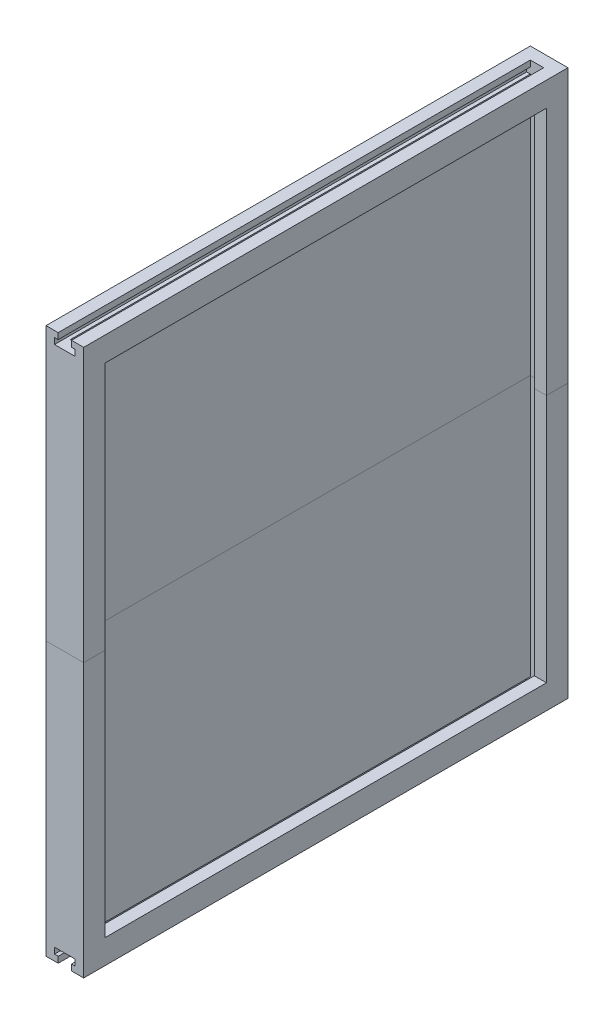
SolidWorks part; units mm, degrees
ref_plane "Front Plane" through (0, 0, 0) normal (1, 0, 0) x (0, 1, 0)
ref_plane "Top Plane" through (0, 0, 0) normal (0, 0, 1) x (0, 1, 0)
ref_plane "Right Plane" through (0, 0, 0) normal (0, 1, 0) x (-1, 0, 0)
sketch "Sketch1" plane through (0, 0, 0) normal (1, 0, 0) x (0, 1, 0)
  line L1 (-225, -199.5) -> (225, -199.5)
  line L2 (-225, -199.5) -> (-225, 199.5)
  line L3 (-225, 199.5) -> (225, 199.5)
  line L4 (225, -199.5) -> (225, 199.5)
  line L5 (-225, -199.5) -> (225, 199.5) construction
  line L6 (-225, 199.5) -> (225, -199.5) construction
  point P0 (0, 0)
  dimension "D1" = 399
  dimension "D2" = 450
extrude "Boss-Extrude1" add sketch "Sketch1" along normal blind 10
sketch "Sketch3" plane through (10, 0, 0) normal (1, 0, 0) x (0, 1, 0)
  line L19 (-225, -199.5) -> (225, -199.5)
  line L20 (-225, -199.5) -> (-225, 199.5)
  line L21 (-225, 199.5) -> (225, 199.5)
  line L22 (225, -199.5) -> (225, 199.5)
  line L23 (-225, -199.5) -> (225, 199.5) construction
  line L24 (-225, 199.5) -> (225, -199.5) construction
  line L25 (-215, -189.5) -> (215, -189.5)
  line L26 (-215, -189.5) -> (-215, 189.5)
  line L27 (-215, 189.5) -> (215, 189.5)
  line L28 (215, -189.5) -> (215, 189.5)
  line L29 (-215, -189.5) -> (215, 189.5) construction
  line L30 (-215, 189.5) -> (215, -189.5) construction
  point P0 (0, 0)
  point P6 (0, 0)
  dimension "D1" = 10
  dimension "D2" = 10
extrude "Boss-Extrude2" add sketch "Sketch3" along normal blind 11
sketch "Sketch5" plane through (21, 0, 0) normal (1, 0, 0) x (0, 1, 0)
  line L1 (-225, -199.5) -> (225, -199.5)
  line L2 (-225, -199.5) -> (-225, 199.5)
  line L3 (-225, 199.5) -> (225, 199.5)
  line L4 (225, -199.5) -> (225, 199.5)
  line L5 (-225, -199.5) -> (225, 199.5) construction
  line L6 (-225, 199.5) -> (225, -199.5) construction
  line L7 (-205, -181.7667) -> (205, -181.7667)
  line L8 (-205, -181.7667) -> (-205, 181.7667)
  line L9 (-205, 181.7667) -> (205, 181.7667)
  line L10 (205, -181.7667) -> (205, 181.7667)
  line L11 (-205, -181.7667) -> (205, 181.7667) construction
  line L12 (-205, 181.7667) -> (205, -181.7667) construction
  point P0 (0, 0)
  point P7 (0, 0)
  dimension "D1" = 20
extrude "Boss-Extrude3" add sketch "Sketch5" along normal blind 10
sketch "Sketch7" plane through (0, 0, 199.5) normal (0, 0, 1) x (1, 0, 0)
  line L0 (0, -215) -> (31, -215) construction
  line L1 (0, 225) -> (0, -225) construction
  line L2 (31, 225) -> (31, -225) construction
  line L3 (31, -225) -> (0, -225) construction
  line L4 (-191.7844, 0) -> (49808.2156, 0) construction
  line L5 (10, -225) -> (21, -225)
  line L6 (10, -225) -> (10, -220)
  line L7 (10, -220) -> (21, -220)
  line L8 (21, -225) -> (21, -220)
  line L9 (24, -220) -> (7, -220)
  line L10 (24, -220) -> (24, -215)
  line L11 (24, -215) -> (7, -215)
  line L12 (7, -220) -> (7, -215)
  line L13 (31, 225) -> (0, 225) construction
  line L14 (0, 215) -> (31, 215) construction
  line L15 (7, 220) -> (7, 215)
  line L16 (24, 215) -> (7, 215)
  line L17 (24, 220) -> (24, 215)
  line L18 (24, 220) -> (7, 220)
  line L19 (21, 225) -> (21, 220)
  line L20 (10, 220) -> (21, 220)
  line L21 (10, 225) -> (10, 220)
  line L22 (10, 225) -> (21, 225)
  line M8 (0, -225) -> (31, -225)
  line M10 (31, 225) -> (0, 225)
  dimension "D1" = 10
  dimension "D2" = 11
  dimension "D3" = 10
  dimension "D4" = 5
  dimension "D5" = 17
  dimension "D6" = 3
  dimension "D7" = 225
extrude "Cut-Extrude1" cut sketch "Sketch7" against normal blind 389 contours L8 L7 L6 M8 | L12 L9 L7 L10 L11 | L21 L18 L19 M10 | L17 L18 L15 L16
sketch "Sketch8" plane through (0, 0, 199.5) normal (0, 0, 1) x (1, 0, 0)
  line L0 (-127.5985, 0) -> (127.5985, 0) construction
  line L2 (0, 0) -> (31, 0)
  line L3 (31, 225) -> (31, -225) construction
  point P4 (0, 0)
split "Split1" trim tools "Sketch8" bodies to split 104 resulting bodies 105 106
equation "\"CD_Height\"= 125mm"
equation "\"CD_Thickness\"= 10mm"
equation "\"CD_Width\"= 142mm"
equation "\"Wall_Thickness\"= 10mm"
equation "\"Total_Height\"= 3 * \"CD_Height\" + 2 * \"Wall_Thickness\" + 4mm"
equation "\"Total_Width\"= \"CD_Width\" * 3 + \"Wall_Thickness\" * 2 + 4mm"
equation "\"Tolerance\"= 1mm"
equation "\"D2@Sketch1\"= \"Total_Width\""
equation "\"D1@Sketch1\"= \"Total_Height\""
equation "\"D1@Sketch3\"=\"Wall_Thickness\""
equation "\"D2@Sketch3\"=\"Wall_Thickness\""
equation "\"D1@Boss-Extrude2\"=\"CD_Thickness\"+\"Tolerance\""
equation "\"Overhang_Width\"= 10mm"
equation "\"D1@Sketch5\"=\"Wall_Thickness\"+\"Overhang_Width\""
equation "\"D1@Boss-Extrude3\"=\"Wall_Thickness\""
equation "\"D1@Sketch7\"=\"Wall_Thickness\""
equation "\"D3@Sketch7\"=\"Wall_Thickness\""
equation "\"D2@Sketch7\"=\"Wall_Thickness\"+1mm"
equation "\"D4@Sketch7\"=\"Wall_Thickness\"/2"
equation "\"D5@Sketch7\"=\"Wall_Thickness\"+1mm+6mm"
equation "\"D7@Sketch7\"=\"Total_Width\"/2"
equation "\"D1@Cut-Extrude1\"=\"Total_Height\"-\"Wall_Thickness\""
